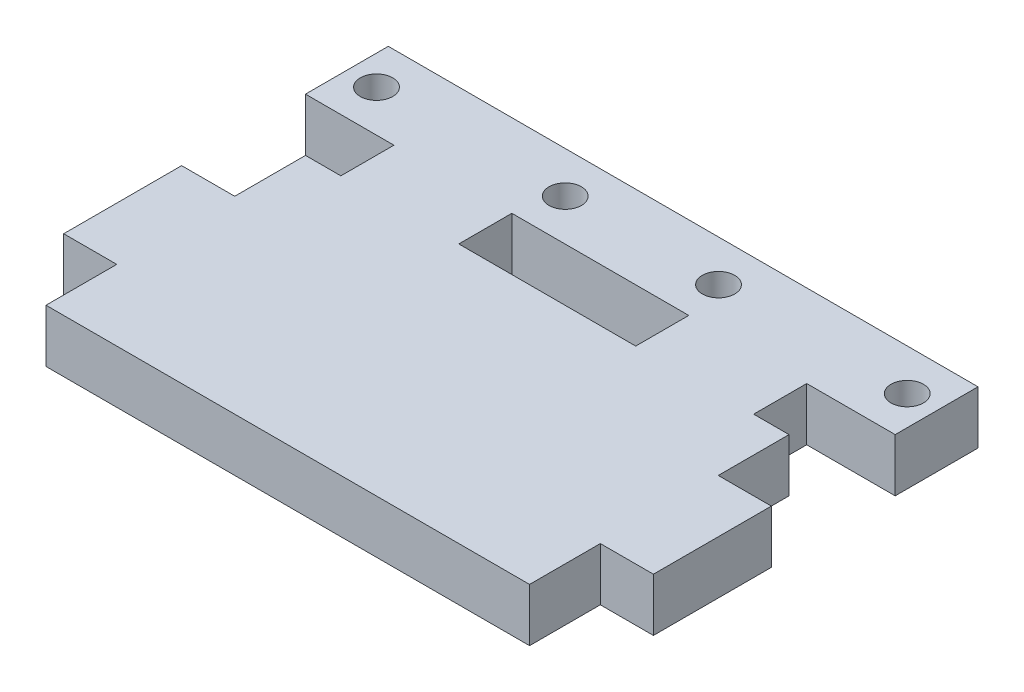
SolidWorks part; units mm, degrees
ref_plane "Front Plane" through (0, 0, 0) normal (0, 0, 1) x (1, 0, 0)
ref_plane "Top Plane" through (0, 0, 0) normal (0, 1, 0) x (1, 0, 0)
ref_plane "Right Plane" through (0, 0, 0) normal (1, 0, 0) x (0, 0, -1)
sketch "Sketch1" plane through (0, 0, 0) normal (0, 1, 0) x (1, 0, 0)
  line L0 (50, -56.0425) -> (50, -100.0425)
  line L2 (-50, -47.0425) -> (-50, -100.0425)
  line L3 (-50, -100.0425) -> (50, -100.0425)
  line L4 (50, -47) -> (50, -47.0425)
  line L6 (-50, -100.0425) -> (-23.5113, -47.0425) construction
  line L7 (-50, -47.0425) -> (50, -47.0425)
  line L8 (-50, -47.0425) -> (35, -47.0425)
  line L9 (-50, -88.0425) -> (-41, -88.0425)
  line L10 (-50, -88.0425) -> (-50, -100.0425)
  line L11 (-50, -100.0425) -> (-41, -100.0425)
  line L12 (-41, -88.0425) -> (-41, -100.0425)
  line L13 (41, -103.0425) -> (50, -103.0425)
  line L14 (-50, -68.0425) -> (-41, -68.0425)
  line L15 (-50, -68.0425) -> (-50, -47.0425)
  line L16 (-50, -47.0425) -> (-41, -47.0425)
  line L17 (-41, -68.0425) -> (-41, -47.0425)
  line L18 (41, -88.0425) -> (41, -103.0425)
  line L19 (-50, -47.0425) -> (-50, -33)
  line L20 (41, -68.0425) -> (41, -56.0425)
  line L21 (50, -88.0425) -> (50, -103.0425)
  line L22 (41, -68.0425) -> (50, -68.0425)
  line L23 (41, -88.0425) -> (50, -88.0425)
  line L24 (50, -68.0425) -> (50, -56.0425)
  line L25 (35, -56.0425) -> (50, -56.0425)
  line L26 (-50, -47.0425) -> (-35, -47.0425)
  line L27 (-50, -47.0425) -> (-50, -56.0425)
  line L28 (-50, -56.0425) -> (-35, -56.0425)
  line L29 (-35, -47.0425) -> (-35, -56.0425)
  line L30 (-50, -33) -> (50, -33)
  line L31 (50, -47) -> (50, -33)
  line L32 (35, -47.0425) -> (35, -56.0425)
  line L35 (-15, -47.0425) -> (15, -47.0425)
  line L36 (-15, -47.0425) -> (-15, -56.0425)
  line L37 (-15, -56.0425) -> (15, -56.0425)
  line L38 (15, -47.0425) -> (15, -56.0425)
  line L39 (0, -47.0425) -> (0, -100.0425) construction
  line L40 (35, -47.0425) -> (50, -100.0425) construction
  point P0 (0, 0)
  point P9 (34.2632, -47.0459)
  point P22 (0, 0)
  point P24 (49.253, -47.0425)
  dimension "D2" = 100
  dimension "D3" = 9
  dimension "D4" = 53
  dimension "D5" = 20
  dimension "D6" = 9
  dimension "D7" = 15
  dimension "D8" = 20
  dimension "D9" = 30
  dimension "D10" = 20
  dimension "D11" = 21
  dimension "D12" = 20
  dimension "D13" = 15
  dimension "D14" = 14
extrude "Boss-Extrude1" add sketch "Sketch1" along normal blind 9
sketch "Sketch3" plane through (0, 9, 0) normal (0, 1, 0) x (1, 0, 0)
  line L0 (-50, -47.0425) -> (-50, -33) construction
  line L1 (-50, -33) -> (50, -33) construction
  line L2 (0, -33) -> (0, -47.0425) construction
  line L3 (-15, -47.0425) -> (15, -47.0425) construction
  circle A0 centre (-45, -40) radius 2.75
  circle A1 centre (-13, -40) radius 2.75
  circle A2 centre (13, -40) radius 2.75
  circle A3 centre (45, -40) radius 2.75
  dimension "D1" = 5.5
  dimension "D3" = 7
  dimension "D4" = 32
  dimension "D5" = 7
  dimension "D6" = 5.5
  dimension "D2" = 5
extrude "Cut-Extrude1" cut sketch "Sketch3" against normal through all
